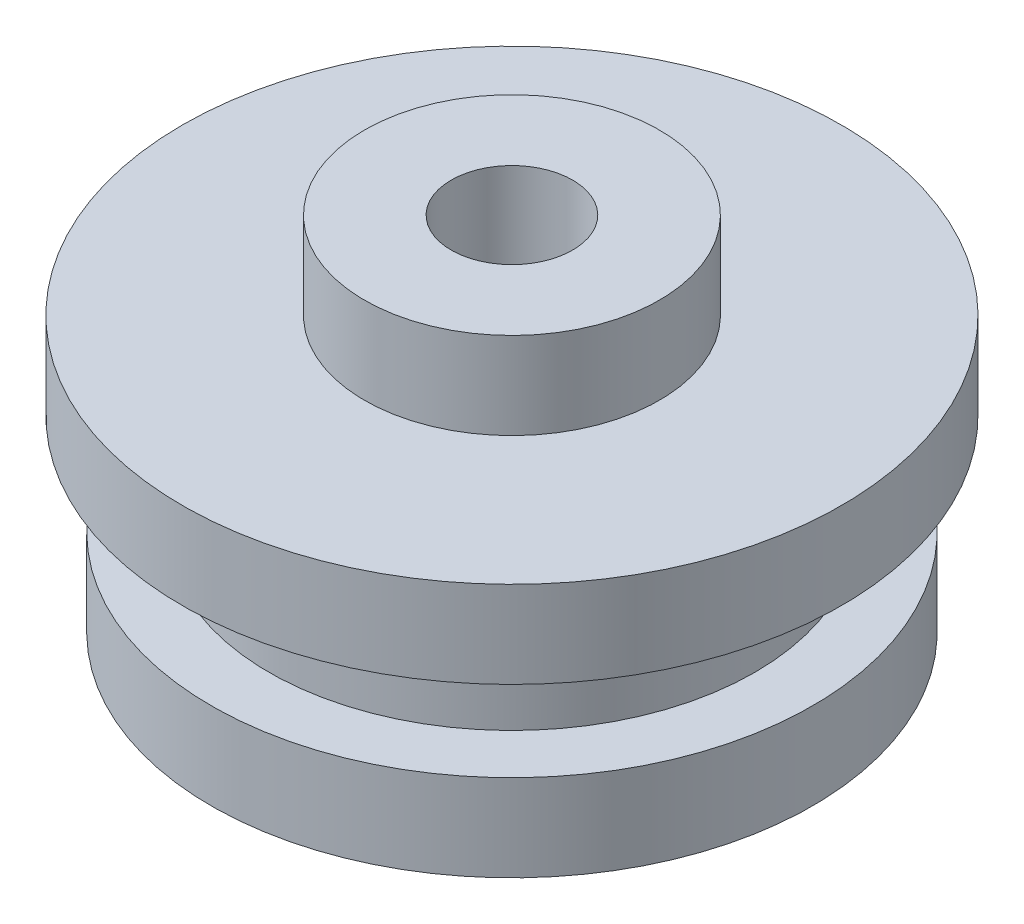
SolidWorks part; units mm, degrees
ref_plane "Plan de face" through (0, 0, 0) normal (0, 0, 1) x (1, 0, 0)
ref_plane "Plan de dessus" through (0, 0, 0) normal (0, 1, 0) x (1, 0, 0)
ref_plane "Plan de droite" through (0, 0, 0) normal (1, 0, 0) x (0, 0, -1)
sketch "Esquisse1" plane through (0, 0, 0) normal (0, 0, 1) x (1, 0, 0)
  line L0 (0, 0) -> (0, -12.5)
  line L1 (0, -12.5) -> (-8.3, -12.5)
  line L2 (-8.3, -12.5) -> (-8.3, -9.5)
  line L3 (-8.3, -9.5) -> (-6.3, -9.5)
  line L4 (-6.3, -9.5) -> (-6.3, -6)
  line L5 (-6.3, -6) -> (-9.3, -6)
  line L6 (-9.3, -6) -> (-9.3, -3)
  line L7 (-9.3, -3) -> (-3, -3)
  line L8 (-3, -3) -> (-3, 0)
  line L9 (-3, 0) -> (0, 0)
  line L10 (2.1, 0) -> (2.1, -12.5) construction
  dimension "D1" = 3
  dimension "D2" = 3
  dimension "D3" = 3
  dimension "D4" = 3.5
  dimension "D5" = 3
  dimension "D6" = 2.1
  dimension "D7" = 8.4
  dimension "D8" = 3
  dimension "D9" = 2
revolve "Révolution1" add sketch "Esquisse1" angle 360 about L10
